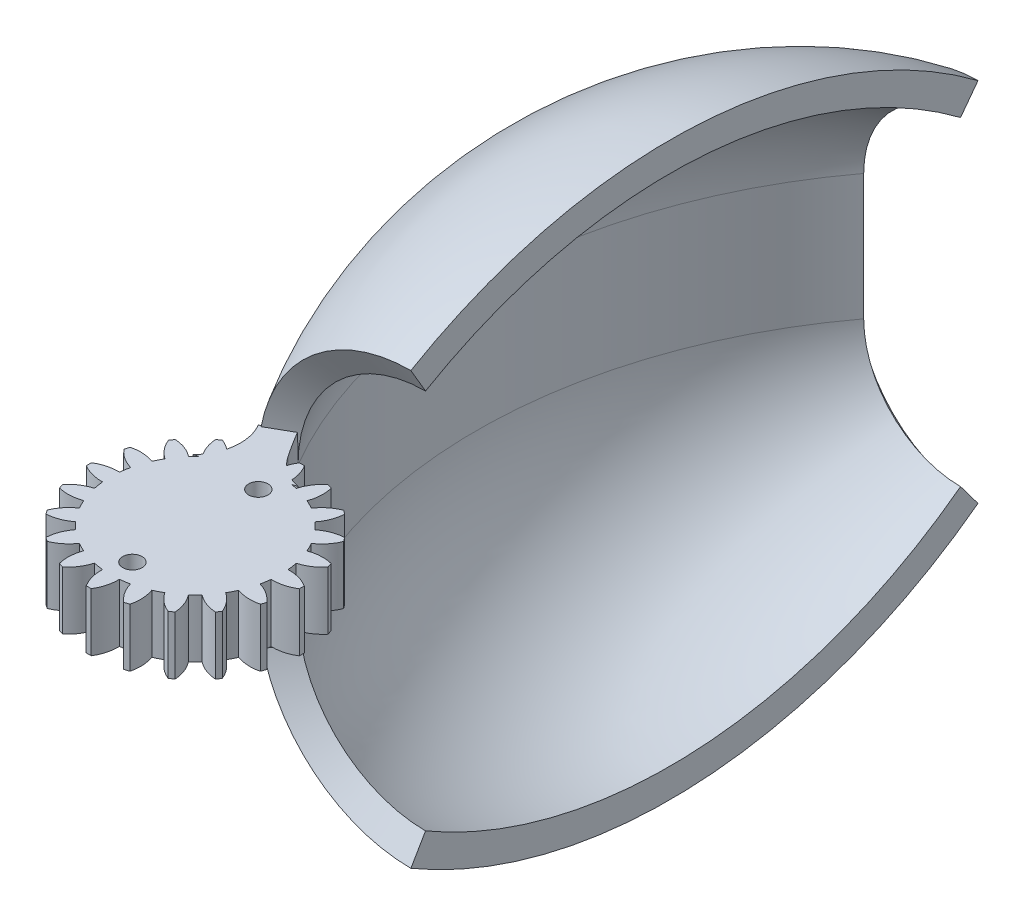
SolidWorks part; units mm, degrees
ref_plane "前视基准面" through (0, 0, 0) normal (0, 0, 1) x (1, 0, 0)
ref_plane "上视基准面" through (0, 0, 0) normal (0, 1, 0) x (1, 0, 0)
ref_plane "右视基准面" through (0, 0, 0) normal (1, 0, 0) x (0, 0, -1)
sketch "草图1" plane through (0, 0, 0) normal (0, 1, 0) x (1, 0, 0)
  line L0 (0, 0) -> (40, 0) construction
  line L1 (0, 42.7058) -> (0, -47.7896) construction
  line L2 (40, 0) -> (0, 30) construction
  line L3 (40, 0) -> (0, -30) construction
  line L4 (-2.4, 31.8) -> (0, 30)
  arc A0 (0, 30) -> (-1.3669, -28.0853) centre (40, 0) ccw
  arc A1 (-2.4, 31.8) -> (-5.7538, -26.7505) centre (40, 0) ccw
  arc A2 (-6.4737, -32.7477) -> (1.7806, -30.1779) centre (0, -39) ccw
  arc A3 (-6.4737, -32.7477) -> (-5.7538, -26.7505) centre (-10.0702, -29.2742) ccw
  arc A4 (1.7806, -30.1779) -> (-1.3669, -28.0853) centre (2.7698, -25.2767) cw
  circle A5 centre (0, -39) radius 1.25
  point P18 (0, -30)
  dimension "D4" = 18
  dimension "D5" = 5
  dimension "D6" = 5
  dimension "D7" = 2.5
  dimension "D1" = 60
  dimension "D2" = 40
  dimension "D3" = 53
extrude "凸台-拉伸2" add sketch "草图1" along normal blind 3
sketch "草图2" plane through (0, 3, 0) normal (0, 1, 0) x (1, 0, 0)
  line L0 (40, 0) -> (-5.7538, -26.7505) construction
  line L1 (-5.7538, -26.7505) -> (-3.1639, -25.2364)
  line L2 (-2.4, 31.8) -> (0, 30)
  line L3 (40, 0) -> (10, 0) construction
  line L4 (10, 9.7418) -> (10, -18.4807) construction
  arc A1 (0, 30) -> (-1.3669, -28.0853) centre (40, 0) ccw construction
  arc A2 (-2.4, 31.8) -> (-5.7538, -26.7505) centre (40, 0) ccw construction
  arc A4 (0, 30) -> (-3.1639, -25.2364) centre (40, 0) ccw
  arc A5 (-2.4, 31.8) -> (-5.7538, -26.7505) centre (40, 0) ccw
  dimension "13" = 30
revolve "旋转6" add sketch "草图2" angle 90 about L4
sketch "草图3" plane through (0, 0, 0) normal (0, -1, 0) x (1, 0, 0)
  line L0 (0, -30) -> (-2.4, -31.8) construction
  line L1 (0, -30) -> (-2.4, -31.8)
  line L2 (40, 0) -> (-5.7538, 26.7505) construction
  line L3 (-5.7538, 26.7505) -> (-3.1639, 25.2364)
  line L4 (40, 0) -> (10, 0) construction
  line L5 (10, 8.9651) -> (10, -7.6873) construction
  arc A0 (-5.7538, 26.7505) -> (-2.4, -31.8) centre (40, 0) ccw construction
  arc A1 (-1.3669, 28.0853) -> (0, -30) centre (40, 0) ccw construction
  arc A2 (-5.7538, 26.7505) -> (-2.4, -31.8) centre (40, 0) ccw
  arc A3 (-3.1639, 25.2364) -> (0, -30) centre (40, 0) ccw
  dimension "D1" = 30
extrude "凸台-拉伸3" add sketch "草图3" along normal blind 10
sketch "草图4" plane through (0, -10, 0) normal (0, -1, 0) x (1, 0, 0)
  line L0 (40, 0) -> (10, 0) construction
  line L1 (10, 0) -> (10, -5.6021) construction
  line L2 (-3.1639, 25.2364) -> (-5.7538, 26.7505)
  line L3 (-2.4, -31.8) -> (0, -30)
  line L4 (-3.1639, 25.2364) -> (-5.7538, 26.7505)
  line L5 (-2.4, -31.8) -> (0, -30)
  arc A2 (-3.1639, 25.2364) -> (0, -30) centre (40, 0) ccw
  arc A3 (-5.7538, 26.7505) -> (-2.4, -31.8) centre (40, 0) ccw
  arc A4 (-3.1639, 25.2364) -> (0, -30) centre (40, 0) ccw
  arc A5 (-5.7538, 26.7505) -> (-2.4, -31.8) centre (40, 0) ccw
  dimension "D2" = 30
  dimension "D1" = 0
revolve "旋转7" add sketch "草图4" angle 90 about L1
sketch "草图5" plane through (0, 0, 0) normal (0, -1, 0) x (1, 0, 0)
  line L0 (-3.1639, 25.2364) -> (-5.7538, 26.7505) construction
  line L1 (-3.1639, 25.2364) -> (-5.7538, 26.7505)
  arc A0 (1.7806, 30.1779) -> (-1.3669, 28.0853) centre (2.7698, 25.2767) ccw construction
  arc A1 (-1.3669, 28.0853) -> (-3.1639, 25.2364) centre (40, 0) ccw construction
  arc A2 (-5.7538, 26.7505) -> (-6.4737, 32.7477) centre (-10.0702, 29.2742) ccw construction
  arc A3 (-1.0392, 28.5157) -> (-1.3669, 28.0853) centre (2.7698, 25.2767) ccw
  arc A4 (-1.3669, 28.0853) -> (-3.1639, 25.2364) centre (40, 0) ccw
  arc A5 (-5.7538, 26.7505) -> (-5.0957, 29.7786) centre (-10.0702, 29.2742) ccw
  arc A6 (-3.6907, 30.7915) -> (-1.6209, 30.1472) centre (0, 39) ccw
  arc A8 (-1.0392, 28.5157) -> (-1.6209, 30.1472) centre (-1.8011, 29.1635) ccw
  arc A9 (-5.0957, 29.7786) -> (-3.6907, 30.7915) centre (-4.1008, 29.8795) cw
  dimension "D1" = 1
extrude "凸台-拉伸4" add sketch "草图5" along normal blind 10
sketch "草图7" plane through (0, 3, 0) normal (0, 1, 0) x (1, 0, 0)
  line L0 (-6.4737, -32.7477) -> (0, -39)
  line L1 (0, -39) -> (1.7806, -30.1779)
  arc A0 (-6.4737, -32.7477) -> (1.7806, -30.1779) centre (0, -39) ccw construction
  arc A1 (-6.4737, -32.7477) -> (1.7806, -30.1779) centre (0, -39) ccw
extrude "切除-拉伸1" cut sketch "草图7" against normal blind 3
sketch "草图8" plane through (0, 3, 0) normal (0, 1, 0) x (1, 0, 0)
  line L0 (-6.4737, -32.7477) -> (1.7806, -30.1779)
  line L4 (-3.1639, -25.2364) -> (-5.7538, -26.7505)
  line L5 (0.2473, -37.7747) -> (1.7806, -30.1779)
  line L7 (-3.1639, -25.2364) -> (-5.7538, -26.7505)
  line L9 (0.2473, -37.7747) -> (1.7806, -30.1779)
  line L10 (-6.4737, -32.7477) -> (-0.8991, -38.1316)
  line L11 (-6.4737, -32.7477) -> (-0.8991, -38.1316)
  arc A4 (-1.3669, -28.0853) -> (1.7806, -30.1779) centre (2.7698, -25.2767) ccw
  arc A5 (-3.1639, -25.2364) -> (-1.3669, -28.0853) centre (40, 0) ccw
  arc A6 (-6.4737, -32.7477) -> (-5.7538, -26.7505) centre (-10.0702, -29.2742) ccw
  arc A7 (0.2473, -37.7747) -> (-0.8991, -38.1316) centre (0, -39) ccw
  arc A8 (-1.3669, -28.0853) -> (1.7806, -30.1779) centre (2.7698, -25.2767) ccw
  arc A9 (-3.1639, -25.2364) -> (-1.3669, -28.0853) centre (40, 0) ccw
  arc A10 (-6.4737, -32.7477) -> (-5.7538, -26.7505) centre (-10.0702, -29.2742) ccw
  arc A12 (0.2473, -37.7747) -> (-0.8991, -38.1316) centre (0, -39) ccw
  arc M9 (1.7806, -30.1779) -> (-1.3669, -28.0853) centre (2.7698, -25.2767) cw
  arc M10 (-1.3669, -28.0853) -> (-3.1639, -25.2364) centre (40, 0) cw
  line M11 (-3.1639, -25.2364) -> (-5.7538, -26.7505)
  arc M12 (-5.7538, -26.7505) -> (-6.4737, -32.7477) centre (-10.0702, -29.2742) cw
  dimension "D1" = 0
extrude "凸台-拉伸6" add sketch "草图8" along normal blind 3 contours L0 M12 M9 M10 M11
sketch "草图6" plane through (0, 3, 0) normal (0, 1, 0) x (1, 0, 0)
  arc A240 (0.2485, -49.9972) -> (0.8647, -47.7062) centre (-3.1324, -47.8595) ccw
  arc A241 (0.8647, -47.7062) -> (1.8524, -47.5507) centre (0, -39) ccw
  arc A242 (1.8524, -47.5507) -> (3.1427, -49.5415) centre (5.7032, -46.4683) ccw
  arc A243 (3.1427, -49.5415) -> (3.6346, -49.3822) centre (0, -39) ccw
  arc A244 (3.6346, -49.3822) -> (3.5127, -47.0129) centre (-0.2413, -48.3938) ccw
  arc A245 (3.5127, -47.0129) -> (4.404, -46.5597) centre (0, -39) ccw
  arc A246 (4.404, -46.5597) -> (6.2464, -48.0544) centre (7.7319, -44.3404) ccw
  arc A247 (6.2464, -48.0544) -> (6.665, -47.7509) centre (0, -39) ccw
  arc A248 (6.665, -47.7509) -> (5.8169, -45.5352) centre (2.6733, -48.0086) ccw
  arc A249 (5.8169, -45.5352) -> (6.5245, -44.8288) centre (0, -39) ccw
  arc A250 (6.5245, -44.8288) -> (8.7387, -45.681) centre (9.0037, -41.6898) ccw
  arc A251 (8.7387, -45.681) -> (9.043, -45.263) centre (0, -39) ccw
  arc A252 (9.043, -45.263) -> (7.5517, -43.4178) centre (5.3263, -46.7416) ccw
  arc A253 (7.5517, -43.4178) -> (8.0064, -42.5274) centre (0, -39) ccw
  arc A254 (8.0064, -42.5274) -> (10.3755, -42.6536) centre (9.3943, -38.7758) ccw
  arc A255 (10.3755, -42.6536) -> (10.5357, -42.162) centre (0, -39) ccw
  arc A256 (10.5357, -42.162) -> (8.5473, -40.868) centre (7.4579, -44.7168) ccw
  arc A257 (8.5473, -40.868) -> (8.7046, -39.8806) centre (0, -39) ccw
  arc A258 (8.7046, -39.8806) -> (10.9967, -39.2686) centre (8.8652, -35.8838) ccw
  arc A259 (10.9967, -39.2686) -> (10.9972, -38.7515) centre (0, -39) ccw
  arc A260 (10.9972, -38.7515) -> (8.7062, -38.1353) centre (8.8595, -42.1324) ccw
  arc A261 (8.7062, -38.1353) -> (8.5507, -37.1476) centre (0, -39) ccw
  arc A262 (8.5507, -37.1476) -> (10.5415, -35.8573) centre (7.4683, -33.2968) ccw
  arc A263 (10.5415, -35.8573) -> (10.3822, -35.3654) centre (0, -39) ccw
  arc A264 (10.3822, -35.3654) -> (8.0129, -35.4873) centre (9.3938, -39.2413) ccw
  arc A265 (8.0129, -35.4873) -> (7.5597, -34.596) centre (0, -39) ccw
  arc A266 (7.5597, -34.596) -> (9.0544, -32.7536) centre (5.3404, -31.2681) ccw
  arc A267 (9.0544, -32.7536) -> (8.7509, -32.335) centre (0, -39) ccw
  arc A268 (8.7509, -32.335) -> (6.5352, -33.1831) centre (9.0086, -36.3267) ccw
  arc A269 (6.5352, -33.1831) -> (5.8288, -32.4755) centre (0, -39) ccw
  arc A270 (5.8288, -32.4755) -> (6.681, -30.2613) centre (2.6898, -29.9963) ccw
  arc A271 (6.681, -30.2613) -> (6.263, -29.957) centre (0, -39) ccw
  arc A272 (6.263, -29.957) -> (4.4178, -31.4483) centre (7.7416, -33.6737) ccw
  arc A273 (4.4178, -31.4483) -> (3.5274, -30.9936) centre (0, -39) ccw
  arc A274 (3.5274, -30.9936) -> (3.6536, -28.6245) centre (-0.2242, -29.6057) ccw
  arc A275 (3.6536, -28.6245) -> (3.162, -28.4643) centre (0, -39) ccw
  arc A276 (3.162, -28.4643) -> (1.868, -30.4527) centre (5.7168, -31.5421) ccw
  arc A277 (1.868, -30.4527) -> (0.8806, -30.2954) centre (0, -39) ccw
  arc A278 (0.8806, -30.2954) -> (0.2686, -28.0033) centre (-3.1162, -30.1348) ccw
  arc A279 (0.2686, -28.0033) -> (-0.2485, -28.0028) centre (0, -39) ccw
  arc A280 (-0.2485, -28.0028) -> (-0.8647, -30.2938) centre (3.1324, -30.1405) ccw
  arc A281 (-0.8647, -30.2938) -> (-1.8524, -30.4493) centre (0, -39) ccw
  arc A282 (-1.8524, -30.4493) -> (-3.1427, -28.4585) centre (-5.7032, -31.5317) ccw
  arc A283 (-3.1427, -28.4585) -> (-3.6346, -28.6178) centre (0, -39) ccw
  arc A284 (-3.6346, -28.6178) -> (-3.5127, -30.9871) centre (0.2413, -29.6062) ccw
  arc A285 (-3.5127, -30.9871) -> (-4.404, -31.4403) centre (0, -39) ccw
  arc A286 (-4.404, -31.4403) -> (-6.2464, -29.9456) centre (-7.7319, -33.6596) ccw
  arc A287 (-6.2464, -29.9456) -> (-6.665, -30.2491) centre (0, -39) ccw
  arc A288 (-6.665, -30.2491) -> (-5.8169, -32.4648) centre (-2.6733, -29.9914) ccw
  arc A289 (-5.8169, -32.4648) -> (-6.5245, -33.1712) centre (0, -39) ccw
  arc A290 (-6.5245, -33.1712) -> (-8.7387, -32.319) centre (-9.0037, -36.3102) ccw
  arc A291 (-8.7387, -32.319) -> (-9.043, -32.737) centre (0, -39) ccw
  arc A292 (-9.043, -32.737) -> (-7.5517, -34.5822) centre (-5.3263, -31.2584) ccw
  arc A293 (-7.5517, -34.5822) -> (-8.0064, -35.4726) centre (0, -39) ccw
  arc A294 (-8.0064, -35.4726) -> (-10.3755, -35.3464) centre (-9.3943, -39.2242) ccw
  arc A295 (-10.3755, -35.3464) -> (-10.5357, -35.838) centre (0, -39) ccw
  arc A296 (-10.5357, -35.838) -> (-8.5473, -37.132) centre (-7.4579, -33.2832) ccw
  arc A297 (-8.5473, -37.132) -> (-8.7046, -38.1194) centre (0, -39) ccw
  arc A298 (-8.7046, -38.1194) -> (-10.9967, -38.7314) centre (-8.8652, -42.1162) ccw
  arc A299 (-10.9967, -38.7314) -> (-10.9972, -39.2485) centre (0, -39) ccw
  arc A300 (-10.9972, -39.2485) -> (-8.7062, -39.8647) centre (-8.8595, -35.8676) ccw
  arc A301 (-8.7062, -39.8647) -> (-8.5507, -40.8524) centre (0, -39) ccw
  arc A302 (-8.5507, -40.8524) -> (-10.5415, -42.1427) centre (-7.4683, -44.7032) ccw
  arc A303 (-10.5415, -42.1427) -> (-10.3822, -42.6346) centre (0, -39) ccw
  arc A304 (-10.3822, -42.6346) -> (-8.0129, -42.5127) centre (-9.3938, -38.7587) ccw
  arc A305 (-8.0129, -42.5127) -> (-7.5597, -43.404) centre (0, -39) ccw
  arc A306 (-7.5597, -43.404) -> (-9.0544, -45.2464) centre (-5.3404, -46.7319) ccw
  arc A307 (-9.0544, -45.2464) -> (-8.7509, -45.665) centre (0, -39) ccw
  arc A308 (-8.7509, -45.665) -> (-6.5352, -44.8169) centre (-9.0086, -41.6733) ccw
  arc A309 (-6.5352, -44.8169) -> (-5.8288, -45.5245) centre (0, -39) ccw
  arc A310 (-5.8288, -45.5245) -> (-6.681, -47.7387) centre (-2.6898, -48.0037) ccw
  arc A311 (-6.681, -47.7387) -> (-6.263, -48.043) centre (0, -39) ccw
  arc A312 (-6.263, -48.043) -> (-4.4178, -46.5517) centre (-7.7416, -44.3263) ccw
  arc A313 (-4.4178, -46.5517) -> (-3.5274, -47.0064) centre (0, -39) ccw
  arc A314 (-3.5274, -47.0064) -> (-3.6536, -49.3755) centre (0.2242, -48.3943) ccw
  arc A315 (-3.6536, -49.3755) -> (-3.162, -49.5357) centre (0, -39) ccw
  arc A316 (-3.162, -49.5357) -> (-1.868, -47.5473) centre (-5.7168, -46.4579) ccw
  arc A317 (-1.868, -47.5473) -> (-0.8806, -47.7046) centre (0, -39) ccw
  arc A318 (-0.8806, -47.7046) -> (-0.2686, -49.9967) centre (3.1162, -47.8652) ccw
  arc A319 (-0.2686, -49.9967) -> (0.2485, -49.9972) centre (0, -39) ccw
  arc A320 (0.2485, -49.9972) -> (0.8647, -47.7062) centre (-3.1324, -47.8595) ccw
  arc A321 (0.8647, -47.7062) -> (1.8524, -47.5507) centre (0, -39) ccw
  arc A322 (1.8524, -47.5507) -> (3.1427, -49.5415) centre (5.7032, -46.4683) ccw
  arc A323 (3.1427, -49.5415) -> (3.6346, -49.3822) centre (0, -39) ccw
  arc A324 (3.6346, -49.3822) -> (3.5127, -47.0129) centre (-0.2413, -48.3938) ccw
  arc A325 (3.5127, -47.0129) -> (4.404, -46.5597) centre (0, -39) ccw
  arc A326 (4.404, -46.5597) -> (6.2464, -48.0544) centre (7.7319, -44.3404) ccw
  arc A327 (6.2464, -48.0544) -> (6.665, -47.7509) centre (0, -39) ccw
  arc A328 (6.665, -47.7509) -> (5.8169, -45.5352) centre (2.6733, -48.0086) ccw
  arc A329 (5.8169, -45.5352) -> (6.5245, -44.8288) centre (0, -39) ccw
  arc A330 (6.5245, -44.8288) -> (8.7387, -45.681) centre (9.0037, -41.6898) ccw
  arc A331 (8.7387, -45.681) -> (9.043, -45.263) centre (0, -39) ccw
  arc A332 (9.043, -45.263) -> (7.5517, -43.4178) centre (5.3263, -46.7416) ccw
  arc A333 (7.5517, -43.4178) -> (8.0064, -42.5274) centre (0, -39) ccw
  arc A334 (8.0064, -42.5274) -> (10.3755, -42.6536) centre (9.3943, -38.7758) ccw
  arc A335 (10.3755, -42.6536) -> (10.5357, -42.162) centre (0, -39) ccw
  arc A336 (10.5357, -42.162) -> (8.5473, -40.868) centre (7.4579, -44.7168) ccw
  arc A337 (8.5473, -40.868) -> (8.7046, -39.8806) centre (0, -39) ccw
  arc A338 (8.7046, -39.8806) -> (10.9967, -39.2686) centre (8.8652, -35.8838) ccw
  arc A339 (10.9967, -39.2686) -> (10.9972, -38.7515) centre (0, -39) ccw
  arc A340 (10.9972, -38.7515) -> (8.7062, -38.1353) centre (8.8595, -42.1324) ccw
  arc A341 (8.7062, -38.1353) -> (8.5507, -37.1476) centre (0, -39) ccw
  arc A342 (8.5507, -37.1476) -> (10.5415, -35.8573) centre (7.4683, -33.2968) ccw
  arc A343 (10.5415, -35.8573) -> (10.3822, -35.3654) centre (0, -39) ccw
  arc A344 (10.3822, -35.3654) -> (8.0129, -35.4873) centre (9.3938, -39.2413) ccw
  arc A345 (8.0129, -35.4873) -> (7.5597, -34.596) centre (0, -39) ccw
  arc A346 (7.5597, -34.596) -> (9.0544, -32.7536) centre (5.3404, -31.2681) ccw
  arc A347 (9.0544, -32.7536) -> (8.7509, -32.335) centre (0, -39) ccw
  arc A348 (8.7509, -32.335) -> (6.5352, -33.1831) centre (9.0086, -36.3267) ccw
  arc A349 (6.5352, -33.1831) -> (5.8288, -32.4755) centre (0, -39) ccw
  arc A350 (5.8288, -32.4755) -> (6.681, -30.2613) centre (2.6898, -29.9963) ccw
  arc A351 (6.681, -30.2613) -> (6.263, -29.957) centre (0, -39) ccw
  arc A352 (6.263, -29.957) -> (4.4178, -31.4483) centre (7.7416, -33.6737) ccw
  arc A353 (4.4178, -31.4483) -> (3.5274, -30.9936) centre (0, -39) ccw
  arc A354 (3.5274, -30.9936) -> (3.6536, -28.6245) centre (-0.2242, -29.6057) ccw
  arc A355 (3.6536, -28.6245) -> (3.162, -28.4643) centre (0, -39) ccw
  arc A356 (3.162, -28.4643) -> (1.868, -30.4527) centre (5.7168, -31.5421) ccw
  arc A357 (1.868, -30.4527) -> (0.8806, -30.2954) centre (0, -39) ccw
  arc A358 (0.8806, -30.2954) -> (0.2686, -28.0033) centre (-3.1162, -30.1348) ccw
  arc A359 (0.2686, -28.0033) -> (-0.2485, -28.0028) centre (0, -39) ccw
  arc A360 (-0.2485, -28.0028) -> (-0.8647, -30.2938) centre (3.1324, -30.1405) ccw
  arc A361 (-0.8647, -30.2938) -> (-1.8524, -30.4493) centre (0, -39) ccw
  arc A362 (-1.8524, -30.4493) -> (-3.1427, -28.4585) centre (-5.7032, -31.5317) ccw
  arc A363 (-3.1427, -28.4585) -> (-3.6346, -28.6178) centre (0, -39) ccw
  arc A364 (-3.6346, -28.6178) -> (-3.5127, -30.9871) centre (0.2413, -29.6062) ccw
  arc A365 (-3.5127, -30.9871) -> (-4.404, -31.4403) centre (0, -39) ccw
  arc A366 (-4.404, -31.4403) -> (-6.2464, -29.9456) centre (-7.7319, -33.6596) ccw
  arc A367 (-6.2464, -29.9456) -> (-6.665, -30.2491) centre (0, -39) ccw
  arc A368 (-6.665, -30.2491) -> (-5.8169, -32.4648) centre (-2.6733, -29.9914) ccw
  arc A369 (-5.8169, -32.4648) -> (-6.5245, -33.1712) centre (0, -39) ccw
  arc A370 (-6.5245, -33.1712) -> (-8.7387, -32.319) centre (-9.0037, -36.3102) ccw
  arc A371 (-8.7387, -32.319) -> (-9.043, -32.737) centre (0, -39) ccw
  arc A372 (-9.043, -32.737) -> (-7.5517, -34.5822) centre (-5.3263, -31.2584) ccw
  arc A373 (-7.5517, -34.5822) -> (-8.0064, -35.4726) centre (0, -39) ccw
  arc A374 (-8.0064, -35.4726) -> (-10.3755, -35.3464) centre (-9.3943, -39.2242) ccw
  arc A375 (-10.3755, -35.3464) -> (-10.5357, -35.838) centre (0, -39) ccw
  arc A376 (-10.5357, -35.838) -> (-8.5473, -37.132) centre (-7.4579, -33.2832) ccw
  arc A377 (-8.5473, -37.132) -> (-8.7046, -38.1194) centre (0, -39) ccw
  arc A378 (-8.7046, -38.1194) -> (-10.9967, -38.7314) centre (-8.8652, -42.1162) ccw
  arc A379 (-10.9967, -38.7314) -> (-10.9972, -39.2485) centre (0, -39) ccw
  arc A380 (-10.9972, -39.2485) -> (-8.7062, -39.8647) centre (-8.8595, -35.8676) ccw
  arc A381 (-8.7062, -39.8647) -> (-8.5507, -40.8524) centre (0, -39) ccw
  arc A382 (-8.5507, -40.8524) -> (-10.5415, -42.1427) centre (-7.4683, -44.7032) ccw
  arc A383 (-10.5415, -42.1427) -> (-10.3822, -42.6346) centre (0, -39) ccw
  arc A384 (-10.3822, -42.6346) -> (-8.0129, -42.5127) centre (-9.3938, -38.7587) ccw
  arc A385 (-8.0129, -42.5127) -> (-7.5597, -43.404) centre (0, -39) ccw
  arc A386 (-7.5597, -43.404) -> (-9.0544, -45.2464) centre (-5.3404, -46.7319) ccw
  arc A387 (-9.0544, -45.2464) -> (-8.7509, -45.665) centre (0, -39) ccw
  arc A388 (-8.7509, -45.665) -> (-6.5352, -44.8169) centre (-9.0086, -41.6733) ccw
  arc A389 (-6.5352, -44.8169) -> (-5.8288, -45.5245) centre (0, -39) ccw
  arc A390 (-5.8288, -45.5245) -> (-6.681, -47.7387) centre (-2.6898, -48.0037) ccw
  arc A391 (-6.681, -47.7387) -> (-6.263, -48.043) centre (0, -39) ccw
  arc A392 (-6.263, -48.043) -> (-4.4178, -46.5517) centre (-7.7416, -44.3263) ccw
  arc A393 (-4.4178, -46.5517) -> (-3.5274, -47.0064) centre (0, -39) ccw
  arc A394 (-3.5274, -47.0064) -> (-3.6536, -49.3755) centre (0.2242, -48.3943) ccw
  arc A395 (-3.6536, -49.3755) -> (-3.162, -49.5357) centre (0, -39) ccw
  arc A396 (-3.162, -49.5357) -> (-1.868, -47.5473) centre (-5.7168, -46.4579) ccw
  arc A397 (-1.868, -47.5473) -> (-0.8806, -47.7046) centre (0, -39) ccw
  arc A398 (-0.8806, -47.7046) -> (-0.2686, -49.9967) centre (3.1162, -47.8652) ccw
  arc A399 (-0.2686, -49.9967) -> (0.2485, -49.9972) centre (0, -39) ccw
  dimension "D1" = 0
extrude "凸台-拉伸7" add sketch "草图6" along normal mid plane 6
sketch "草图9" plane through (0, 0, 0) normal (0, -1, 0) x (1, 0, 0)
  line L0 (0, 32.5) -> (0, 45.5) construction
  circle A0 centre (0, 45.5) radius 1
  circle A1 centre (0, 39) radius 1.25
  circle A2 centre (0, 39) radius 1.25 construction
  circle A3 centre (0, 32.5) radius 1
  point P7 (0, 39)
  dimension "D3" = 2
  dimension "D4" = 2
  dimension "D2" = 13
  dimension "D1" = 0
extrude "切除-拉伸2" cut sketch "草图9" against normal through all
